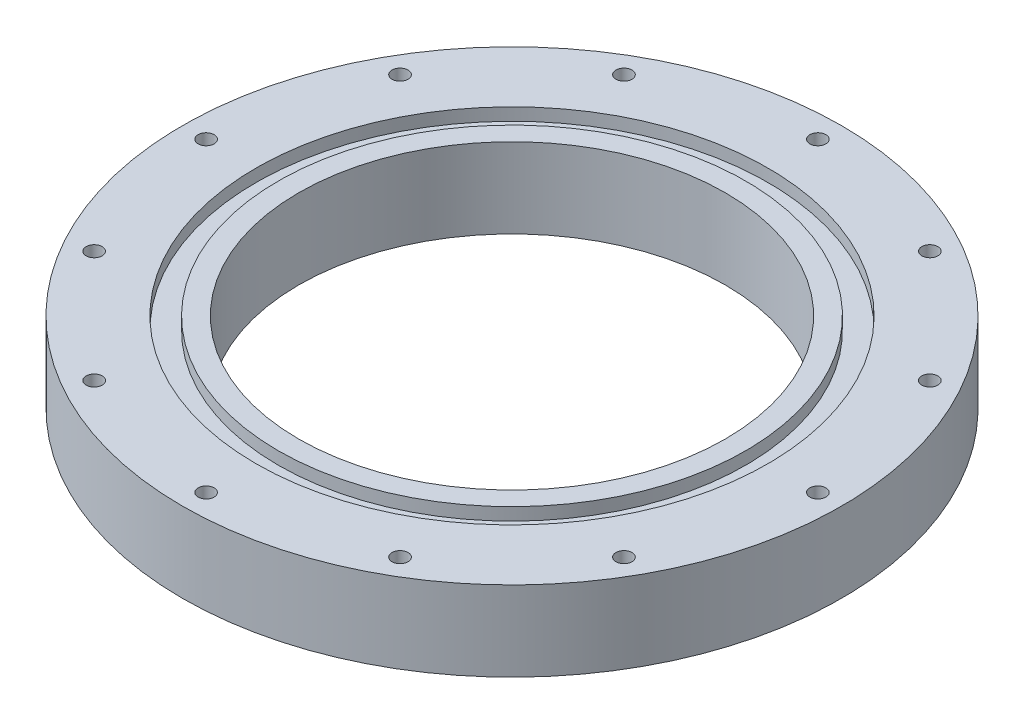
SolidWorks part; units mm, degrees
ref_plane "Front Plane" through (0, 0, 0) normal (0, 0, 1) x (1, 0, 0)
ref_plane "Top Plane" through (0, 0, 0) normal (0, 1, 0) x (1, 0, 0)
ref_plane "Right Plane" through (0, 0, 0) normal (1, 0, 0) x (0, 0, -1)
sketch "Sketch2" plane through (0, 0, 0) normal (0, 1, 0) x (1, 0, 0)
  circle A2 centre (0, 0) radius 104.775
  circle A3 centre (0, 0) radius 67.818
  dimension "D1" = 209.55
  dimension "D2" = 135.636
extrude "Flange" add sketch "Sketch2" along normal blind 25.4
sketch "Sketch4" plane through (0, 25.4, 0) normal (0, 1, 0) x (1, 0, 0)
  line L0 (0, 75.8825) -> (0, 81.2165) construction
  circle A3 centre (0, 0) radius 81.407
  circle A4 centre (0, 0) radius 74.295
  point P7 (0, 78.5495)
  dimension "D1" = 148.59
  dimension "D2" = 7.112
  dimension "D3" = 2.667
extrude "Groove" cut sketch "Sketch4" against normal blind 3.9878
sketch "Sketch5" plane through (0, 25.4, 0) normal (0, 1, 0) x (1, 0, 0)
  line L0 (89.7255, 0) -> (104.775, 0) construction
  circle A0 centre (0, 0) radius 97.2503 construction
  circle A1 centre (0, -97.2503) radius 3.175 construction
  circle A3 centre (0, -97.2503) radius 2.5527
  circle A6 centre (0, 0) radius 89.7255 construction
  circle A7 centre (0, 0) radius 104.775 construction
  point P9 (97.2503, 0)
  dimension "D1" = 5.1054
  dimension "D2" = 179.451
  dimension "D3" = 6.35
extrude "Screw Holes" cut sketch "Sketch5" against normal up to surface (25.4 mm away) up to face at (0, 0, 104.775)
pattern_circular "CirPattern1" count 12 over 360 about axis through (0, 0, 0) along (0, 1, 0) of "Screw Holes"
sketch "Sketch6" plane through (0, 25.4, 0) normal (0, 1, 0) x (1, 0, 0)
  circle A0 centre (0, 0) radius 89.7255
  dimension "D1" = 179.451
